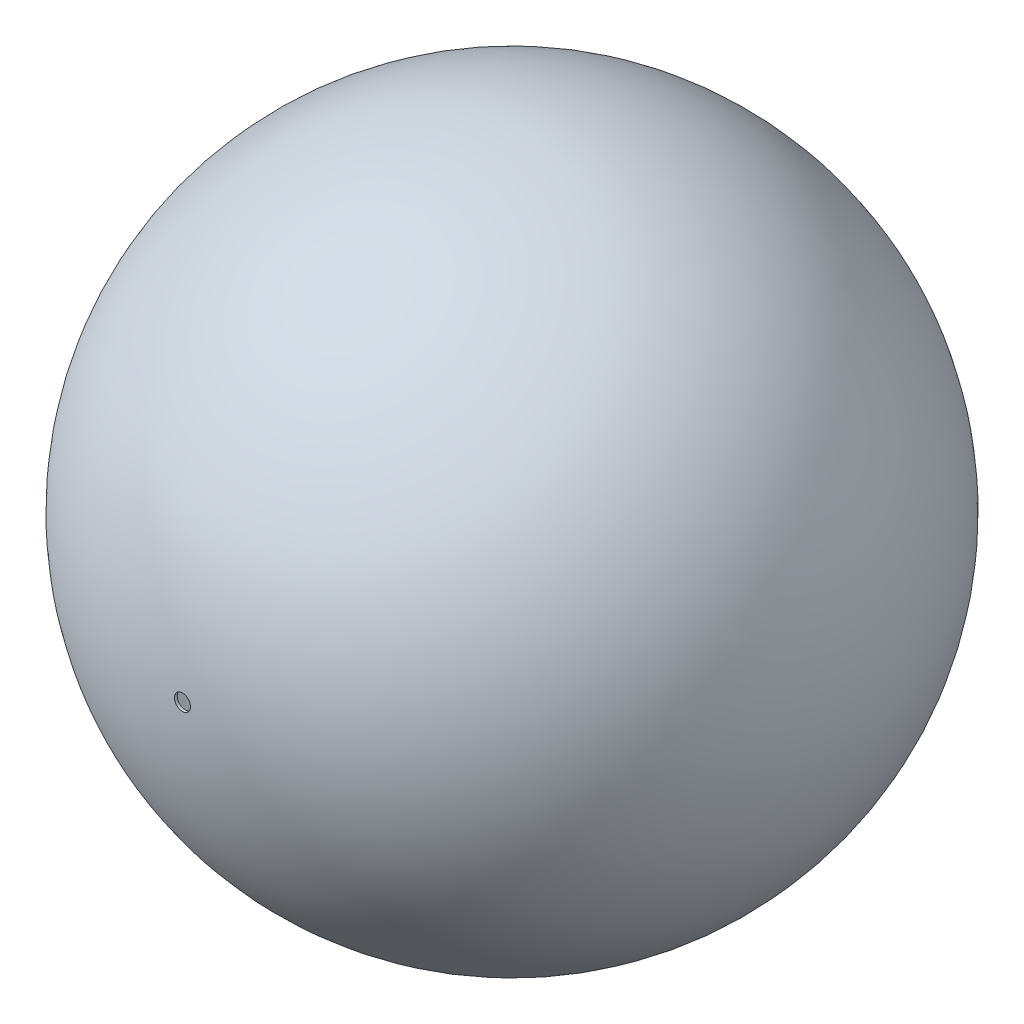
SolidWorks part; units mm, degrees
material "Inconel 718"
ref_plane "Front Plane" through (0, 0, 0) normal (0, 0, 1) x (1, 0, 0)
ref_plane "Top Plane" through (0, 0, 0) normal (0, 1, 0) x (1, 0, 0)
ref_plane "Right Plane" through (0, 0, 0) normal (1, 0, 0) x (0, 0, -1)
sketch "Sketch1" plane through (0, 0, 0) normal (0, 0, 1) x (1, 0, 0)
  line L1 (-228.6, 0) -> (-226.695, 0)
  line L2 (226.695, 0) -> (228.6, 0)
  arc A0 (228.6, 0) -> (-228.6, 0) centre (0, 0) ccw
  arc A1 (226.695, 0) -> (-226.695, 0) centre (0, 0) ccw
  dimension "D1" = 457.2
  dimension "D2" = 453.39
ref_axis "Axis3" through (0, 0, 0) along (1, 0, 0)
revolve "Revolve6" add sketch "Sketch1" angle 180 about axis through (0, 0, 0) along (1, 0, 0)
sketch "Sketch2" plane through (0, 0, -254) normal (0, 0, 1) x (-0.934, -0.3571, 0)
  circle A0 centre (0, 0) radius 5.5562
  dimension "D1" = 11.1125
extrude "Cut-Extrude1" cut sketch "Sketch2" against normal through all both and the other way through all
mirror "Mirror1" about plane through (0, 0, 0) normal (0, 0, 1) of bodies 103
equation "\"D2@Sketch1\"=18-2*.075in"
